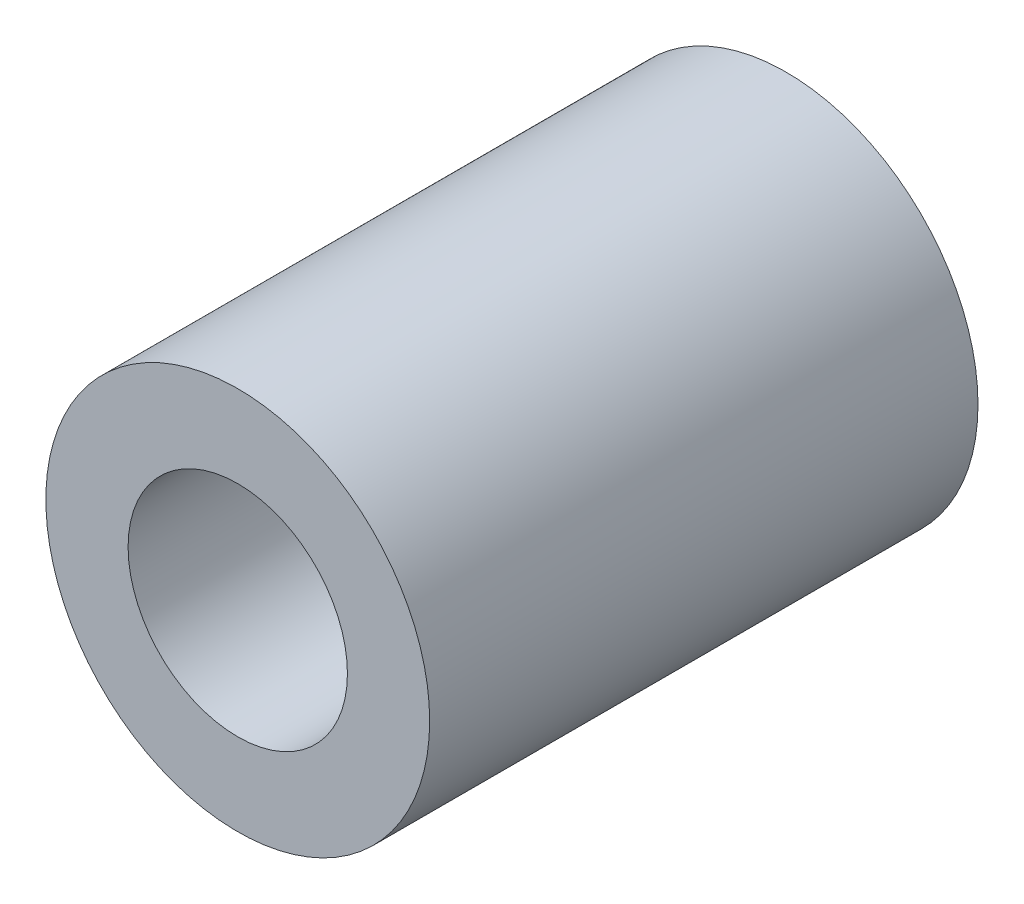
SolidWorks part; units mm, degrees
ref_plane "Front Plane" through (0, 0, 0) normal (0, 0, 1) x (1, 0, 0)
ref_plane "Top Plane" through (0, 0, 0) normal (0, 1, 0) x (1, 0, 0)
ref_plane "Right Plane" through (0, 0, 0) normal (1, 0, 0) x (0, 0, -1)
sketch "Sketch1" plane through (0, 0, 0) normal (0, 0, 1) x (1, 0, 0)
  circle A0 centre (0, 0) radius 6
  circle A1 centre (0, 0) radius 10.5
  dimension "D1" = 21
  dimension "D2" = 12
extrude "Boss-Extrude1" add sketch "Sketch1" along normal blind 30
